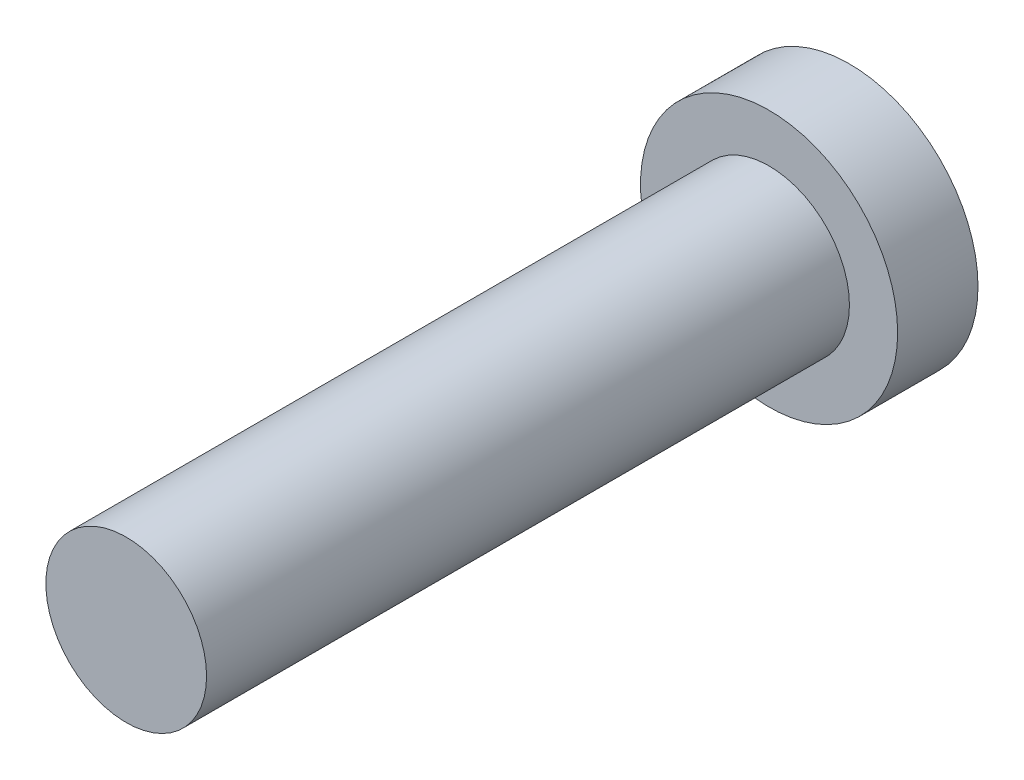
SolidWorks part; units mm, degrees
ref_plane "Front Plane" through (0, 0, 0) normal (0, 0, 1) x (1, 0, 0)
ref_plane "Top Plane" through (0, 0, 0) normal (0, 1, 0) x (1, 0, 0)
ref_plane "Right Plane" through (0, 0, 0) normal (1, 0, 0) x (0, 0, -1)
sketch "Sketch1" plane through (0, 0, 0) normal (0, 0, 1) x (1, 0, 0)
  circle A0 centre (0, 0) radius 8
  dimension "D1" = 16
extrude "Boss-Extrude1" add sketch "Sketch1" along normal blind 5
sketch "Sketch2" plane through (0, 0, 5) normal (0, 0, 1) x (1, 0, 0)
  circle A0 centre (0, 0) radius 5
  dimension "D1" = 10
extrude "Boss-Extrude2" add sketch "Sketch2" along normal blind 40
